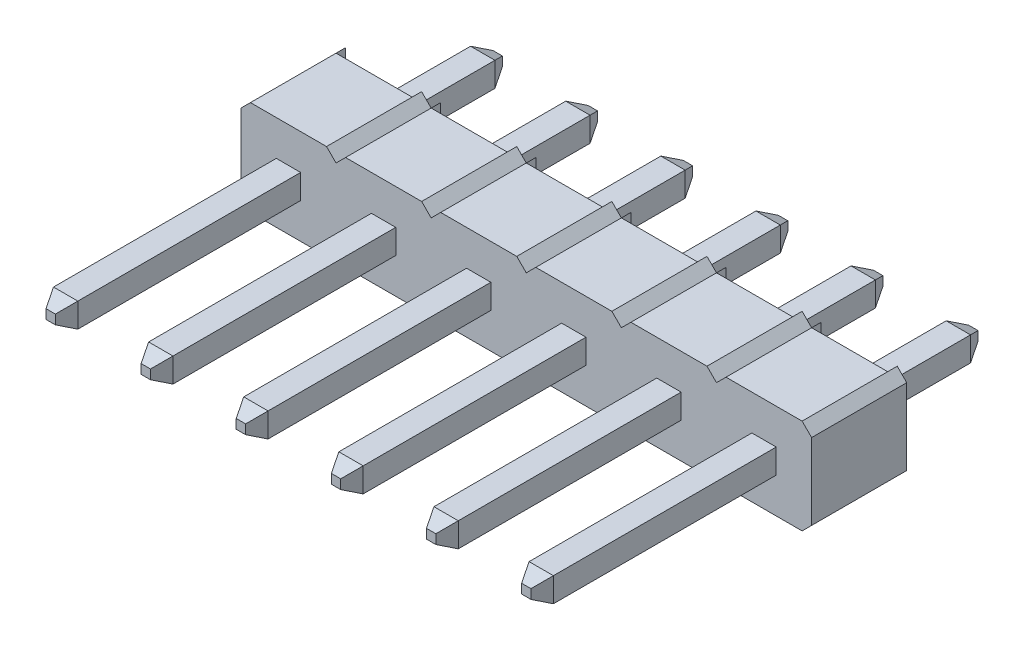
SolidWorks part; units mm, degrees
ref_plane "Front Plane" through (0, 0, 0) normal (0, 0, 1) x (1, 0, 0)
ref_plane "Top Plane" through (0, 0, 0) normal (0, 1, 0) x (1, 0, 0)
ref_plane "Right Plane" through (0, 0, 0) normal (1, 0, 0) x (0, 0, -1)
ref_plane "Plane1" through (0, 0, 2.54) normal (0, 0, 1) x (1, 0, 0)
sketch "Sketch1" plane through (0, 0, 2.54) normal (0, 0, 1) x (1, 0, 0)
  line L0 (13.97, -1.016) -> (13.97, 1.016)
  line L1 (13.97, 1.016) -> (13.716, 1.27)
  line L2 (13.716, 1.27) -> (11.684, 1.27)
  line L3 (11.684, 1.27) -> (11.43, 1.016)
  line L4 (11.43, 1.016) -> (11.176, 1.27)
  line L5 (11.176, 1.27) -> (9.144, 1.27)
  line L6 (9.144, 1.27) -> (8.89, 1.016)
  line L7 (8.89, 1.016) -> (8.636, 1.27)
  line L8 (8.636, 1.27) -> (6.604, 1.27)
  line L9 (6.604, 1.27) -> (6.35, 1.016)
  line L10 (6.35, 1.016) -> (6.096, 1.27)
  line L11 (6.096, 1.27) -> (4.064, 1.27)
  line L12 (4.064, 1.27) -> (3.81, 1.016)
  line L13 (3.81, 1.016) -> (3.556, 1.27)
  line L14 (3.556, 1.27) -> (1.524, 1.27)
  line L15 (1.524, 1.27) -> (1.27, 1.016)
  line L16 (1.27, 1.016) -> (1.016, 1.27)
  line L17 (1.016, 1.27) -> (-1.016, 1.27)
  line L18 (-1.016, 1.27) -> (-1.27, 1.016)
  line L19 (-1.27, 1.016) -> (-1.27, -1.016)
  line L20 (-1.27, -1.016) -> (-1.016, -1.27)
  line L21 (-1.016, -1.27) -> (1.016, -1.27)
  line L22 (1.016, -1.27) -> (1.27, -1.016)
  line L23 (1.27, -1.016) -> (1.524, -1.27)
  line L24 (1.524, -1.27) -> (3.556, -1.27)
  line L25 (3.556, -1.27) -> (3.81, -1.016)
  line L26 (3.81, -1.016) -> (4.064, -1.27)
  line L27 (4.064, -1.27) -> (6.096, -1.27)
  line L28 (6.096, -1.27) -> (6.35, -1.016)
  line L29 (6.35, -1.016) -> (6.604, -1.27)
  line L30 (6.604, -1.27) -> (8.636, -1.27)
  line L31 (8.636, -1.27) -> (8.89, -1.016)
  line L32 (8.89, -1.016) -> (9.144, -1.27)
  line L33 (9.144, -1.27) -> (11.176, -1.27)
  line L34 (11.176, -1.27) -> (11.43, -1.016)
  line L35 (11.43, -1.016) -> (11.684, -1.27)
  line L36 (11.684, -1.27) -> (13.716, -1.27)
  line L37 (13.716, -1.27) -> (13.97, -1.016)
extrude "Boss-Extrude1" add sketch "Sketch1" against normal blind 2.286
sketch "Sketch2" plane through (0, 0, 0.254) normal (0, 0, -1) x (-1, 0, 0)
  line L0 (-6.604, -1.27) -> (-6.604, 1.27)
  line L1 (-6.604, 1.27) -> (-6.35, 1.016)
  line L2 (-6.35, 1.016) -> (-6.096, 1.27)
  line L3 (-6.096, 1.27) -> (-6.096, -1.27)
  line L4 (-6.096, -1.27) -> (-6.35, -1.016)
  line L5 (-6.35, -1.016) -> (-6.604, -1.27)
extrude "Boss-Extrude2" add sketch "Sketch2" along normal blind 0.254
sketch "Sketch3" plane through (0, 0, 0.254) normal (0, 0, -1) x (-1, 0, 0)
  line L0 (-9.144, -1.27) -> (-9.144, 1.27)
  line L1 (-9.144, 1.27) -> (-8.89, 1.016)
  line L2 (-8.89, 1.016) -> (-8.636, 1.27)
  line L3 (-8.636, 1.27) -> (-8.636, -1.27)
  line L4 (-8.636, -1.27) -> (-8.89, -1.016)
  line L5 (-8.89, -1.016) -> (-9.144, -1.27)
extrude "Boss-Extrude3" add sketch "Sketch3" along normal blind 0.254
sketch "Sketch4" plane through (0, 0, 0.254) normal (0, 0, -1) x (-1, 0, 0)
  line L0 (-11.684, -1.27) -> (-11.684, 1.27)
  line L1 (-11.684, 1.27) -> (-11.43, 1.016)
  line L2 (-11.43, 1.016) -> (-11.176, 1.27)
  line L3 (-11.176, 1.27) -> (-11.176, -1.27)
  line L4 (-11.176, -1.27) -> (-11.43, -1.016)
  line L5 (-11.43, -1.016) -> (-11.684, -1.27)
extrude "Boss-Extrude4" add sketch "Sketch4" along normal blind 0.254
sketch "Sketch5" plane through (0, 0, 0.254) normal (0, 0, -1) x (-1, 0, 0)
  line L0 (-4.064, -1.27) -> (-4.064, 1.27)
  line L1 (-4.064, 1.27) -> (-3.81, 1.016)
  line L2 (-3.81, 1.016) -> (-3.556, 1.27)
  line L3 (-3.556, 1.27) -> (-3.556, -1.27)
  line L4 (-3.556, -1.27) -> (-3.81, -1.016)
  line L5 (-3.81, -1.016) -> (-4.064, -1.27)
extrude "Boss-Extrude5" add sketch "Sketch5" along normal blind 0.254
sketch "Sketch6" plane through (0, 0, 0.254) normal (0, 0, -1) x (-1, 0, 0)
  line L0 (-1.524, -1.27) -> (-1.524, 1.27)
  line L1 (-1.524, 1.27) -> (-1.27, 1.016)
  line L2 (-1.27, 1.016) -> (-1.016, 1.27)
  line L3 (-1.016, 1.27) -> (-1.016, -1.27)
  line L4 (-1.016, -1.27) -> (-1.27, -1.016)
  line L5 (-1.27, -1.016) -> (-1.524, -1.27)
extrude "Boss-Extrude6" add sketch "Sketch6" along normal blind 0.254
sketch "Sketch7" plane through (0, 0, 0.254) normal (0, 0, -1) x (-1, 0, 0)
  line L0 (1.016, -1.27) -> (1.016, 1.27)
  line L1 (1.016, 1.27) -> (1.27, 1.016)
  line L2 (1.27, 1.016) -> (1.27, -1.016)
  line L3 (1.27, -1.016) -> (1.016, -1.27)
extrude "Boss-Extrude7" add sketch "Sketch7" along normal blind 0.254
sketch "Sketch8" plane through (0, 0, 0.254) normal (0, 0, -1) x (-1, 0, 0)
  line L0 (-13.97, -1.016) -> (-13.97, 1.016)
  line L1 (-13.97, 1.016) -> (-13.716, 1.27)
  line L2 (-13.716, 1.27) -> (-13.716, -1.27)
  line L3 (-13.716, -1.27) -> (-13.97, -1.016)
extrude "Boss-Extrude8" add sketch "Sketch8" along normal blind 0.254
sketch "Sketch9" plane through (0, 0, 0.254) normal (0, 0, -1) x (-1, 0, 0)
  line L0 (0.325, 0.325) -> (0.325, -0.325)
  line L1 (0.325, -0.325) -> (-0.325, -0.325)
  line L2 (-0.325, -0.325) -> (-0.325, 0.325)
  line L3 (-0.325, 0.325) -> (0.325, 0.325)
extrude "Boss-Extrude9" add sketch "Sketch9" along normal blind 3.302
sketch "Sketch10" plane through (0, 0, 2.54) normal (0, 0, 1) x (1, 0, 0)
  line L0 (-0.325, -0.325) -> (-0.325, 0.325)
  line L1 (-0.325, 0.325) -> (0.325, 0.325)
  line L2 (0.325, 0.325) -> (0.325, -0.325)
  line L3 (0.325, -0.325) -> (-0.325, -0.325)
extrude "Boss-Extrude10" add sketch "Sketch10" along normal blind 6.35
sketch "Sketch11" plane through (0, 0, 0.254) normal (0, 0, -1) x (-1, 0, 0)
  line L0 (-12.375, -0.325) -> (-13.025, -0.325)
  line L1 (-13.025, -0.325) -> (-13.025, 0.325)
  line L2 (-13.025, 0.325) -> (-12.375, 0.325)
  line L3 (-12.375, 0.325) -> (-12.375, -0.325)
extrude "Boss-Extrude11" add sketch "Sketch11" along normal blind 3.302
sketch "Sketch12" plane through (0, 0, 2.54) normal (0, 0, 1) x (1, 0, 0)
  line L0 (12.375, -0.325) -> (12.375, 0.325)
  line L1 (12.375, 0.325) -> (13.025, 0.325)
  line L2 (13.025, 0.325) -> (13.025, -0.325)
  line L3 (13.025, -0.325) -> (12.375, -0.325)
extrude "Boss-Extrude12" add sketch "Sketch12" along normal blind 6.35
sketch "Sketch13" plane through (0, 0, 0.254) normal (0, 0, -1) x (-1, 0, 0)
  line L0 (-9.835, -0.325) -> (-10.485, -0.325)
  line L1 (-10.485, -0.325) -> (-10.485, 0.325)
  line L2 (-10.485, 0.325) -> (-9.835, 0.325)
  line L3 (-9.835, 0.325) -> (-9.835, -0.325)
extrude "Boss-Extrude13" add sketch "Sketch13" along normal blind 3.302
sketch "Sketch14" plane through (0, 0, 2.54) normal (0, 0, 1) x (1, 0, 0)
  line L0 (9.835, -0.325) -> (9.835, 0.325)
  line L1 (9.835, 0.325) -> (10.485, 0.325)
  line L2 (10.485, 0.325) -> (10.485, -0.325)
  line L3 (10.485, -0.325) -> (9.835, -0.325)
extrude "Boss-Extrude14" add sketch "Sketch14" along normal blind 6.35
sketch "Sketch15" plane through (0, 0, 0.254) normal (0, 0, -1) x (-1, 0, 0)
  line L0 (-7.945, 0.325) -> (-7.295, 0.325)
  line L1 (-7.295, 0.325) -> (-7.295, -0.325)
  line L2 (-7.295, -0.325) -> (-7.945, -0.325)
  line L3 (-7.945, -0.325) -> (-7.945, 0.325)
extrude "Boss-Extrude15" add sketch "Sketch15" along normal blind 3.302
sketch "Sketch16" plane through (0, 0, 2.54) normal (0, 0, 1) x (1, 0, 0)
  line L0 (7.945, 0.325) -> (7.945, -0.325)
  line L1 (7.945, -0.325) -> (7.295, -0.325)
  line L2 (7.295, -0.325) -> (7.295, 0.325)
  line L3 (7.295, 0.325) -> (7.945, 0.325)
extrude "Boss-Extrude16" add sketch "Sketch16" along normal blind 6.35
sketch "Sketch17" plane through (0, 0, 0.254) normal (0, 0, -1) x (-1, 0, 0)
  line L0 (-5.405, 0.325) -> (-4.755, 0.325)
  line L1 (-4.755, 0.325) -> (-4.755, -0.325)
  line L2 (-4.755, -0.325) -> (-5.405, -0.325)
  line L3 (-5.405, -0.325) -> (-5.405, 0.325)
extrude "Boss-Extrude17" add sketch "Sketch17" along normal blind 3.302
sketch "Sketch18" plane through (0, 0, 2.54) normal (0, 0, 1) x (1, 0, 0)
  line L0 (5.405, 0.325) -> (5.405, -0.325)
  line L1 (5.405, -0.325) -> (4.755, -0.325)
  line L2 (4.755, -0.325) -> (4.755, 0.325)
  line L3 (4.755, 0.325) -> (5.405, 0.325)
extrude "Boss-Extrude18" add sketch "Sketch18" along normal blind 6.35
sketch "Sketch19" plane through (0, 0, 0.254) normal (0, 0, -1) x (-1, 0, 0)
  line L0 (-2.865, 0.325) -> (-2.215, 0.325)
  line L1 (-2.215, 0.325) -> (-2.215, -0.325)
  line L2 (-2.215, -0.325) -> (-2.865, -0.325)
  line L3 (-2.865, -0.325) -> (-2.865, 0.325)
extrude "Boss-Extrude19" add sketch "Sketch19" along normal blind 3.302
sketch "Sketch20" plane through (0, 0, 2.54) normal (0, 0, 1) x (1, 0, 0)
  line L0 (2.865, 0.325) -> (2.865, -0.325)
  line L1 (2.865, -0.325) -> (2.215, -0.325)
  line L2 (2.215, -0.325) -> (2.215, 0.325)
  line L3 (2.215, 0.325) -> (2.865, 0.325)
extrude "Boss-Extrude20" add sketch "Sketch20" along normal blind 6.35
chamfer "Chamfer1" distance 0.2 angle 63.435 48 edges at (7.62, -0.325, 8.89) (7.945, 0, 8.89) (7.295, 0, 8.89) (7.62, 0.325, 8.89) (2.54, -0.325, 8.89) (2.865, 0, 8.89) (2.54, 0.325, 8.89) (2.215, 0, 8.89) (5.08, -0.325, 8.89) (5.405, 0, 8.89) (5.08, 0.325, 8.89) (4.755, 0, 8.89) (0, -0.325, -3.048) (-0.325, 0, -3.048) (0, 0.325, -3.048) (0.325, 0, -3.048) (7.295, 0, -3.048) (7.62, -0.325, -3.048) (7.62, 0.325, -3.048) (7.945, 0, -3.048) (4.755, 0, -3.048) (5.08, -0.325, -3.048) (5.08, 0.325, -3.048) (5.405, 0, -3.048) (2.215, 0, -3.048) (2.54, -0.325, -3.048) (2.54, 0.325, -3.048) (2.865, 0, -3.048) (0, 0.325, 8.89) (0.325, 0, 8.89) (-0.325, 0, 8.89) (0, -0.325, 8.89) (13.025, 0, -3.048) (12.7, -0.325, -3.048) (12.375, 0, -3.048) (12.7, 0.325, -3.048) (12.7, 0.325, 8.89) (13.025, 0, 8.89) (12.375, 0, 8.89) (12.7, -0.325, 8.89) (10.485, 0, -3.048) (10.16, -0.325, -3.048) (9.835, 0, -3.048) (10.16, 0.325, -3.048) (10.16, 0.325, 8.89) (10.485, 0, 8.89) (9.835, 0, 8.89) (10.16, -0.325, 8.89)
